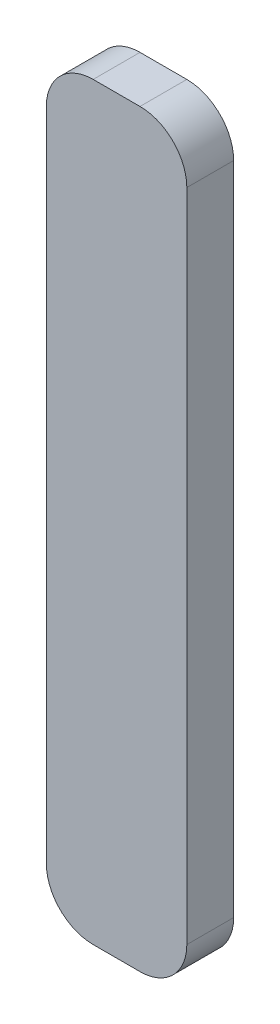
SolidWorks part; units mm, degrees
ref_plane "Přední rovina" through (0, 0, 0) normal (0, 0, 1) x (1, 0, 0)
ref_plane "Horní rovina" through (0, 0, 0) normal (0, 1, 0) x (1, 0, 0)
ref_plane "Pravá rovina" through (0, 0, 0) normal (1, 0, 0) x (0, 0, -1)
sketch "Skica1" plane through (0, 0, 0) normal (0, 0, 1) x (1, 0, 0)
  line L1 (0, 0) -> (30, 0)
  line L2 (0, 0) -> (0, 160)
  line L3 (0, 160) -> (30, 160)
  line L4 (30, 0) -> (30, 160)
  dimension "D1" = 160
  dimension "D2" = 30
extrude "Přidat vysunutím1" add sketch "Skica1" along normal blind 10
fillet "Zaoblit1" radius 10 4 edges at (30, 0, 5) (0, 0, 5) (30, 160, 5) (0, 160, 5)
